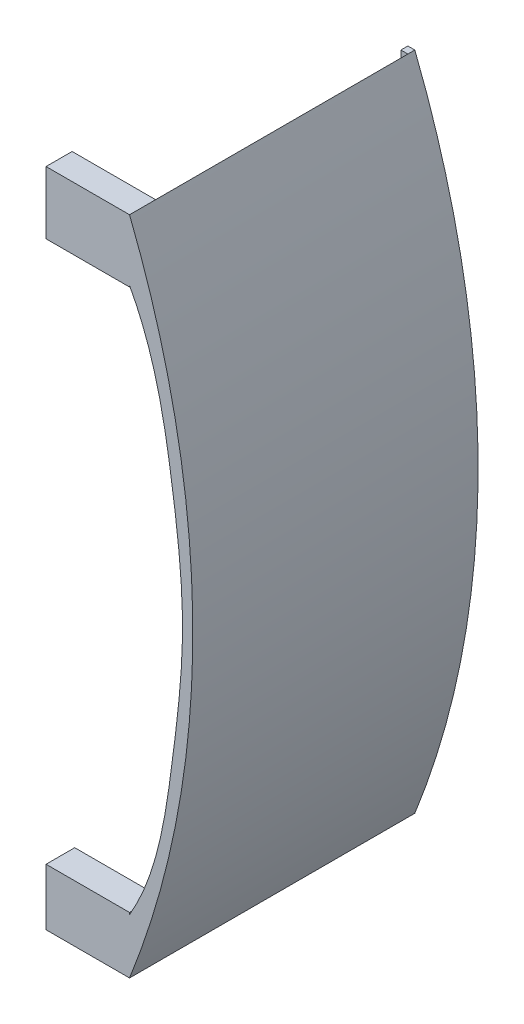
SolidWorks part; units mm, degrees
ref_plane "Front Plane" through (0, 0, 0) normal (0, 0, 1) x (1, 0, 0)
ref_plane "Top Plane" through (0, 0, 0) normal (0, 1, 0) x (1, 0, 0)
ref_plane "Right Plane" through (0, 0, 0) normal (1, 0, 0) x (0, 0, -1)
sketch "Sketch5" plane through (0, 0, 0) normal (0, 0, 1) x (1, 0, 0)
  line L0 (0, -95) -> (0, 95)
  line L2 (0, -44.275) -> (0, 44.275) construction
  arc A0 (0, 95) -> (0, -95) centre (-238.9883, 0) cw
  point P4 (0, 0)
  dimension "D1" = 190
extrude "Boss-Extrude2" add sketch "Sketch5" along normal mid plane 82
sketch "Sketch6" plane through (0, 0, 0) normal (0, 0, 1) x (1, 0, 0)
  line L0 (0, 73.1891) -> (0, -75.9354)
  line L2 (0, -44.275) -> (0, 44.275) construction
  arc A0 (0, 73.1891) -> (0, -75.9354) centre (-228.681, -1.3732) cw
extrude "Cut-Extrude1" cut sketch "Sketch6" against normal through all both and the other way through all
sketch "Sketch7" plane through (0, 0, 0) normal (-1, 0, 0) x (0, 0, 1)
  line L2 (41, 95) -> (33.508, 95)
  line L3 (41, 95) -> (41, 77)
  line L4 (41, 77) -> (33.508, 77)
  line L5 (33.508, 95) -> (33.508, 77)
  dimension "D1" = 18
  dimension "D2" = 7.492
extrude "Boss-Extrude3" add sketch "Sketch7" along normal blind 24
sketch "Sketch9" plane through (0, 0, 0) normal (-1, 0, 0) x (0, 0, 1)
  line L1 (41, -95) -> (32.758, -95)
  line L2 (41, -95) -> (41, -78.6817)
  line L3 (41, -78.6817) -> (32.758, -78.6817)
  line L4 (32.758, -95) -> (32.758, -78.6817)
extrude "Boss-Extrude4" add sketch "Sketch9" along normal blind 24
sketch "Sketch12" plane through (0, 0, 0) normal (0, 0, 1) x (1, 0, 0)
  line L0 (-27.0523, 0) -> (18.1895, 0)
  arc A0 (0, -95) -> (0, 95) centre (-238.9883, 0) ccw construction
sketch "Sketch14" plane through (0, 0, 0) normal (1, 0, 0) x (0, 0, -1)
  line L0 (0, 0) -> (41, 0)
ref_plane "Plane2" through (0, 0, -41) normal (0, 0, 1) x (1, 0, 0)
sketch "Sketch15" plane through (0, 0, -41) normal (0, 0, 1) x (1, 0, 0)
  line L1 (0, 95) -> (-2, 95)
  line L2 (0, 95) -> (0, 73.1891)
  line L3 (0, 73.1891) -> (-2, 73.1891)
  line L4 (-2, 95) -> (-2, 73.1891)
extrude "Boss-Extrude6" add sketch "Sketch15" along normal blind 2
sketch "Sketch16" plane through (0, 0, -41) normal (0, 0, 1) x (1, 0, 0)
  line L1 (0, -95) -> (-2, -95)
  line L2 (0, -95) -> (0, -75.9354)
  line L3 (0, -75.9354) -> (-2, -75.9354)
  line L4 (-2, -95) -> (-2, -75.9354)
extrude "Boss-Extrude7" add sketch "Sketch16" along normal blind 2
ref_plane "Plane3" through (-27.0523, 0, 0) normal (1, 0, 0) x (0, 0, -1)
sketch "Sketch17" plane through (-27.0523, 0, 0) normal (1, 0, 0) x (0, 0, -1)
  line L0 (39, -75.9354) -> (-41, -75.9354) construction
  line L1 (39, 73.1891) -> (-38.8282, 73.1891)
  line L2 (39, 73.1891) -> (39, -75.9354)
  line L3 (39, -75.9354) -> (-38.8282, -75.9354)
  line L4 (-38.8282, 73.1891) -> (-38.8282, -75.9354)
sketch "Sketch18" plane through (0, 0, 0) normal (0, 0, 1) x (1, 0, 0)
  line L0 (0, 77.404) -> (0, -79.2332)
  line L1 (0, -44.275) -> (0, 44.275) construction
  line L3 (-27.0523, 0) -> (18.1895, 0) construction
  spline S0 degree 3 poles (0, 77.404) (7.2997, 63.9991) (12.0699, 37.6791) (16.5809, -0.0418) (12.0147, -38.3104) (8.0947, -65.4561) (0, -79.2332) knots 0 0 0 0 0.282271 0.494146 0.70669 1 1 1 1
extrude "Cut-Extrude2" cut sketch "Sketch18" against normal through all both and the other way through all
